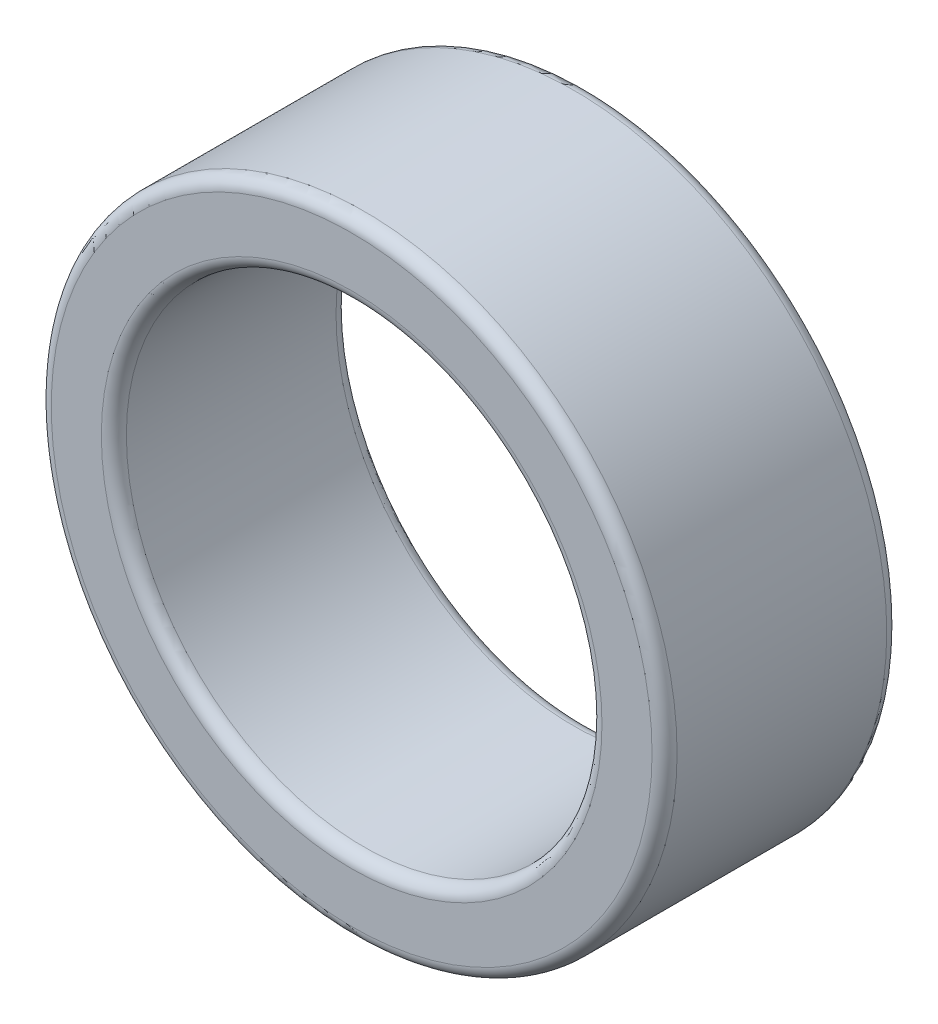
SolidWorks part; units mm, degrees
ref_plane "Front Plane" through (0, 0, 0) normal (0, 0, 1) x (1, 0, 0)
ref_plane "Top Plane" through (0, 0, 0) normal (0, 1, 0) x (1, 0, 0)
ref_plane "Right Plane" through (0, 0, 0) normal (1, 0, 0) x (0, 0, -1)
sketch "Sketch1" plane through (0, 0, 0) normal (0, 0, 1) x (1, 0, 0)
  circle A0 centre (0, 0) radius 9.652
  circle A1 centre (0, 0) radius 12.7
  dimension "D1" = 25.4
  dimension "D2" = 19.304
extrude "Boss-Extrude1" add sketch "Sketch1" along normal blind 9.525
fillet "Fillet1" radius 0.508 4 edges at (12.7, 0, 0) (12.7, 0, 9.525) (9.652, 0, 0) (9.652, 0, 9.525)
